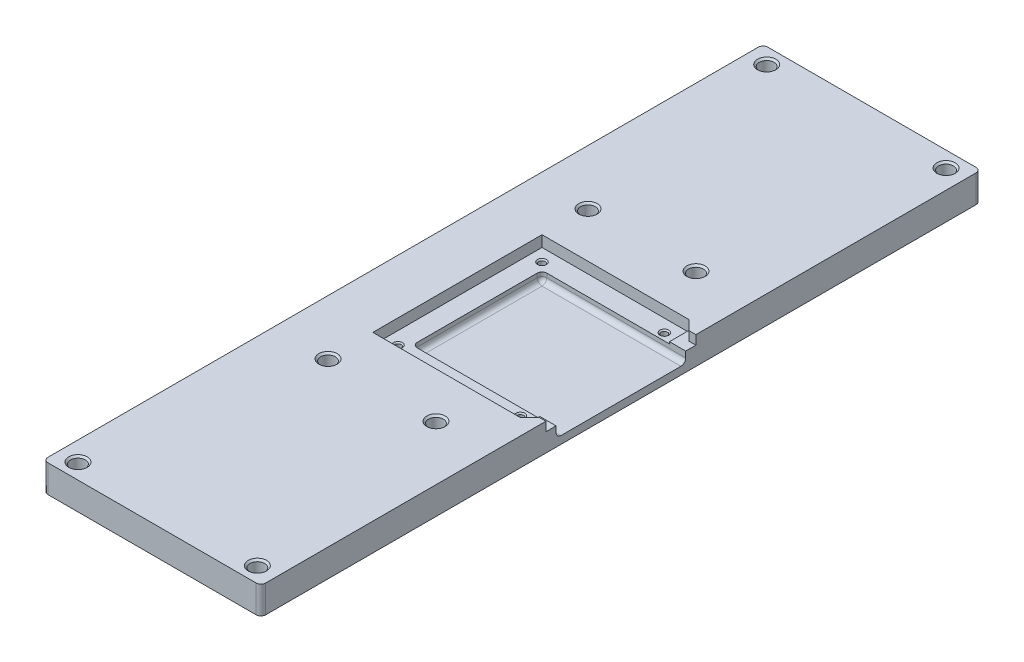
SolidWorks part; units mm, degrees
ref_plane "Front Plane" through (0, 0, 0) normal (0, 0, 1) x (1, 0, 0)
ref_plane "Top Plane" through (0, 0, 0) normal (0, 1, 0) x (1, 0, 0)
ref_plane "Right Plane" through (0, 0, 0) normal (1, 0, 0) x (0, 0, -1)
sketch "Sketch1" plane through (0, 0, 0) normal (0, 1, 0) x (1, 0, 0)
  line L0 (0, -135) -> (0, 135) construction
  line L1 (45.375, 135) -> (-45.375, 135) construction
  line L2 (-45.375, 135) -> (-45.375, -135)
  line L3 (-45.375, 0) -> (45.375, 0) construction
  line L4 (-45.375, 135) -> (-45.375, 148)
  line L5 (-43.375, 150) -> (43.375, 150)
  line L6 (0, 150) -> (0, 135) construction
  line L7 (45.375, 135) -> (45.375, 148)
  line L8 (45.375, 135) -> (45.375, -135)
  line L9 (0, -150) -> (0, -135) construction
  line L10 (45.375, -135) -> (-45.375, -135) construction
  line L11 (45.375, -135) -> (45.375, -148)
  line L12 (-43.375, -150) -> (43.375, -150)
  line L13 (-45.375, -135) -> (-45.375, -148)
  line L14 (-45.375, 138) -> (45.375, 138) construction
  circle A1 centre (-37.375, 143.5) radius 3.075 construction
  circle A2 centre (37.375, 143.5) radius 3.075 construction
  circle A5 centre (37.375, -143.5) radius 3.075 construction
  circle A6 centre (-37.375, -143.5) radius 3.075 construction
  arc A8 (-43.375, -150) -> (-45.375, -148) centre (-43.375, -148) cw
  arc A9 (45.375, -148) -> (43.375, -150) centre (43.375, -148) cw
  arc A10 (45.375, 148) -> (43.375, 150) centre (43.375, 148) ccw
  arc A11 (-45.375, 148) -> (-43.375, 150) centre (-43.375, 148) cw
  circle A12 centre (-22.5, 54.175) radius 3.075 construction
  circle A13 centre (22.5, 54.175) radius 3.075 construction
  circle A14 centre (22.5, -54.175) radius 3.075 construction
  circle A15 centre (-22.5, -54.175) radius 3.075 construction
  point P24 (0, 0)
  point P36 (-45.375, -150)
  point P39 (45.375, -150)
  point P42 (45.375, 150)
  point P45 (-45.375, 150)
  dimension "D5" = 22.5
  dimension "D10" = 2
  dimension "D3" = 6.15
  dimension "D1" = 45.375
  dimension "D2" = 135
  dimension "D4" = 6.5
  dimension "D6" = 8
  dimension "D7" = 8.5
  dimension "D8" = 12
  dimension "D9" = 3
  dimension "D11" = 150
  dimension "D12" = 54.175
extrude "Boss-Extrude1" add sketch "Sketch1" along normal blind 11.5
sketch "Sketch3" plane through (0, 11.5, 0) normal (0, 1, 0) x (1, 0, 0)
  line L0 (0, 0) -> (-45.375, 0) construction
  line L1 (-45.375, 148) -> (-45.375, -148) construction
  line L2 (0, 0) -> (0, 150) construction
  line L3 (43.375, 150) -> (-43.375, 150) construction
  line L4 (3.96, -16.3) -> (3.96, 16.3)
  line L5 (-2.46, -17.8) -> (2.46, -17.8)
  line L6 (-3.96, 16.3) -> (-3.96, -16.3)
  line L7 (2.46, 17.8) -> (-2.46, 17.8)
  line L8 (0, 17.8) -> (0, -17.8) construction
  line L9 (13.25, 0) -> (0, 0) construction
  line L10 (16.15, 10.025) -> (10.35, 10.025)
  line L11 (16.15, 10.025) -> (16.15, -10.025)
  line L12 (16.15, -10.025) -> (10.35, -10.025)
  line L13 (10.35, 10.025) -> (10.35, -10.025)
  line L14 (16.15, 10.025) -> (10.35, -10.025) construction
  line L15 (16.15, -10.025) -> (10.35, 10.025) construction
  line L16 (13.25, 0) -> (13.25, 10.025) construction
  line L17 (-16.15, 10.025) -> (-16.15, -10.025)
  line L18 (-16.15, -10.025) -> (-10.35, -10.025)
  line L23 (-16.15, 10.025) -> (-10.35, 10.025)
  line L24 (-10.35, 10.025) -> (-10.35, -10.025)
  arc A0 (-2.46, 17.8) -> (-3.96, 16.3) centre (-2.46, 16.3) ccw
  arc A1 (3.96, 16.3) -> (2.46, 17.8) centre (2.46, 16.3) ccw
  arc A2 (2.46, -17.8) -> (3.96, -16.3) centre (2.46, -16.3) ccw
  arc A3 (-3.96, -16.3) -> (-2.46, -17.8) centre (-2.46, -16.3) ccw
  point P9 (0, 0)
  point P23 (0, 0)
  dimension "D2" = 1.5
  dimension "D1" = 35.6
  dimension "D3" = 7.92
  dimension "D4" = 20.05
  dimension "D5" = 5.8
  dimension "D6" = 13.25
sketch "Sketch4" plane through (0, 11.5, 0) normal (0, 1, 0) x (1, 0, 0)
  circle A0 centre (-37.375, -143.5) radius 3.075 construction
  circle A1 centre (37.375, -143.5) radius 3.075 construction
  circle A2 centre (37.375, 143.5) radius 3.075 construction
  circle A3 centre (-22.5, -54.175) radius 3.075 construction
  circle A4 centre (22.5, -54.175) radius 3.075 construction
  circle A5 centre (-37.375, 143.5) radius 3.075 construction
  circle A6 centre (22.5, 54.175) radius 3.075 construction
  circle A7 centre (-22.5, 54.175) radius 3.075 construction
  circle A8 centre (-37.375, -143.5) radius 3.075
  circle A9 centre (37.375, -143.5) radius 3.075
  circle A10 centre (37.375, 143.5) radius 3.075
  circle A13 centre (-37.375, 143.5) radius 3.075
  circle A14 centre (-22.5, -54.175) radius 3.075
  circle A15 centre (22.5, -54.175) radius 3.075
  circle A16 centre (22.5, 54.175) radius 3.075
  circle A17 centre (-22.5, 54.175) radius 3.075
extrude "Cut-Extrude1" cut sketch "Sketch4" against normal blind 6
sketch "Sketch21" plane through (0, 11.5, 0) normal (0, 1, 0) x (1, 0, 0)
  line L0 (38.5, 35) -> (-22.5, 35) construction
  line L1 (38.5, 35) -> (42.5, 31) construction
  line L2 (-22.5, 35) -> (-22.5, -35) construction
  line L3 (-22.5, 0) -> (0, 0) construction
  line L4 (0, 0) -> (38.5, 0) construction
  line L5 (38.5, -35) -> (38.5, 35) construction
  line L6 (38.5, -35) -> (-22.5, -35) construction
  line L7 (42.5, 31) -> (45.375, 31) construction
  line L8 (45.375, -148) -> (45.375, 148) construction
  line L9 (45.375, 31) -> (45.375, -31)
  line L10 (45.375, 0) -> (38.5, 0) construction
  line L11 (42.5, -31) -> (45.375, -31) construction
  line L12 (38.5, -35) -> (42.5, -31) construction
  line L13 (42.6036, 31.25) -> (45.375, 31.25)
  line L14 (38.6036, 35.25) -> (42.6036, 31.25)
  line L15 (38.6036, 35.25) -> (-22.75, 35.25)
  line L16 (-22.75, 35.25) -> (-22.75, -35.25)
  line L17 (38.6036, -35.25) -> (-22.75, -35.25)
  line L18 (38.6036, -35.25) -> (42.6036, -31.25)
  line L19 (42.6036, -31.25) -> (45.375, -31.25)
  line L20 (45.375, -31.25) -> (45.375, -31)
  line L21 (45.375, 31) -> (45.375, 31.25)
  circle A0 centre (-17.5, 30) radius 1.6 construction
  circle A1 centre (33.5, 30) radius 1.6 construction
  circle A2 centre (33.5, -30) radius 1.6 construction
  circle A3 centre (-17.5, -30) radius 1.6 construction
  dimension "D8" = 3.2
  dimension "D1" = 22.5
  dimension "D2" = 61
  dimension "D3" = 35
  dimension "D4" = 5
  dimension "D5" = 5
  dimension "D6" = 5
  dimension "D7" = 5
  dimension "D9" = 45
  dimension "D10" = 4
  dimension "D12" = 2.875
  dimension "D11" = 0.25
extrude "Cut-Extrude6" cut sketch "Sketch21" against normal blind 4.6
sketch "Sketch24" plane through (0, 6.9, 0) normal (0, 1, 0) x (1, 0, 0)
  line L0 (45.375, 27) -> (-14.5, 27)
  line L2 (-14.5, 27) -> (-14.5, -27)
  line L3 (-14.5, -27) -> (45.375, -27)
  line L4 (45.375, -27) -> (45.375, 27)
  line L8 (38.5, 35) -> (-22.5, 35) construction
  line L10 (-22.5, 35) -> (-22.5, -35) construction
  line L11 (38.5, -35) -> (-22.5, -35) construction
  line L12 (45.375, -31.25) -> (45.375, 31.25) construction
  dimension "D1" = 8
  dimension "D2" = 8
  dimension "D3" = 8
extrude "Cut-Extrude3" cut sketch "Sketch24" against normal blind 3.7 and the other way through all
sketch "Sketch25" plane through (0, 6.9, 0) normal (0, 1, 0) x (1, 0, 0)
  circle A0 centre (33.5, 30) radius 1.35
  circle A1 centre (-17.5, 30) radius 1.35
  circle A2 centre (33.5, -30) radius 1.35
  circle A3 centre (-17.5, -30) radius 1.35
  dimension "D1" = 2.7
extrude "Cut-Extrude4" cut sketch "Sketch25" against normal blind 5
chamfer "Chamfer4" distance 0.5 angle 45 4 edges at (-17.5, 6.9, 31.35) (33.5, 6.9, 31.35) (33.5, 6.9, -28.65) (-17.5, 6.9, -28.65)
fillet "Fillet1" radius 2 5 edges at (15.4375, 3.2, 27) (-14.5, 5.05, 27) (-14.5, 5.05, -27) (-14.5, 3.2, 0) (15.4375, 3.2, -27)
sketch "Sketch26" plane through (0, 6.9, 0) normal (0, 1, 0) x (1, 0, 0)
  line L0 (0, 0) -> (45.375, 0) construction
  line L1 (45.375, -25) -> (45.375, 25) construction
  line L2 (38.6036, 35.25) -> (38.6036, 27)
  line L3 (45.375, 27) -> (-12.5, 27) construction
  line L4 (38.6036, 27) -> (45.375, 27)
  line L5 (45.375, 27) -> (45.375, 31.25)
  line L6 (45.375, 31.25) -> (42.6036, 31.25)
  line L7 (42.6036, 31.25) -> (38.6036, 35.25)
  line L8 (42.6036, -31.25) -> (38.6036, -35.25)
  line L9 (45.375, -31.25) -> (42.6036, -31.25)
  line L10 (45.375, -27) -> (45.375, -31.25)
  line L11 (38.6036, -27) -> (45.375, -27)
  line L12 (38.6036, -35.25) -> (38.6036, -27)
extrude "Boss-Extrude2" add sketch "Sketch26" along normal blind 0.8
chamfer "Chamfer5" distance 0.75 angle 45 8 edges at (37.375, 11.5, -140.425) (-37.375, 11.5, -140.425) (-22.5, 11.5, -51.1) (22.5, 11.5, -51.1) (22.5, 11.5, 57.25) (-22.5, 11.5, 57.25) (-37.375, 11.5, 146.575) (37.375, 11.5, 146.575)
equation "\"D5@Sketch21\"=\"D4@Sketch21\""
equation "\"D6@Sketch21\"=\"D4@Sketch21\""
equation "\"D7@Sketch21\"=\"D4@Sketch21\""
equation "\"D2@Sketch24\"=\"D1@Sketch24\""
equation "\"D3@Sketch24\"=\"D1@Sketch24\""
